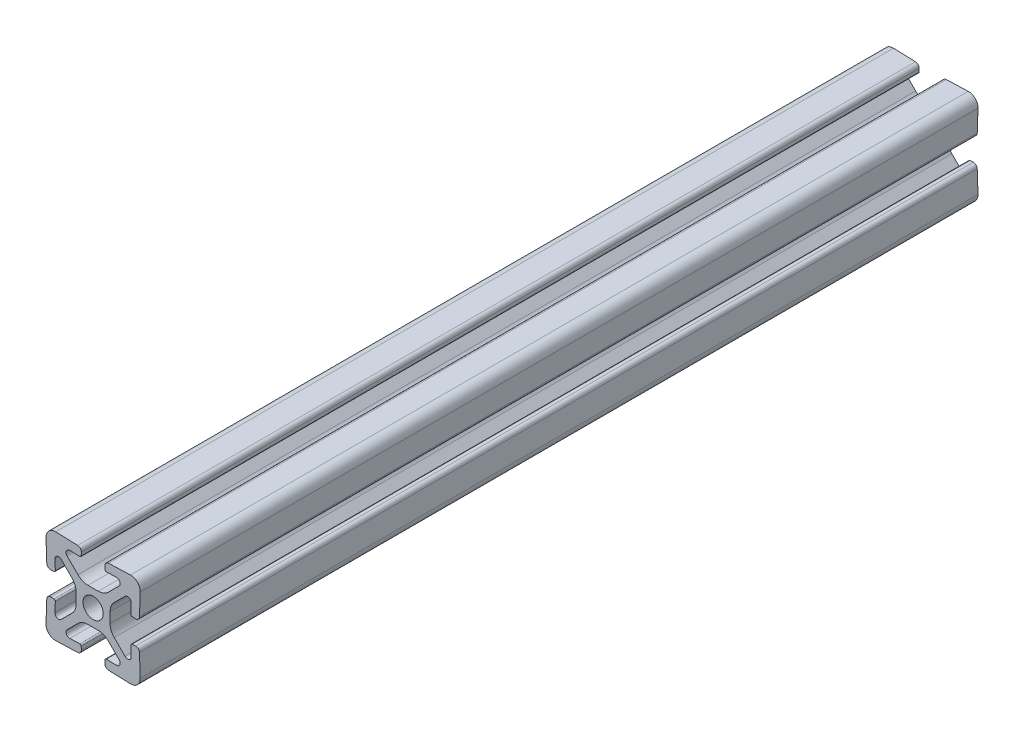
SolidWorks part; units mm, degrees
ref_plane "Front Plane" through (0, 0, 0) normal (0, 0, 1) x (1, 0, 0)
ref_plane "Top Plane" through (0, 0, 0) normal (0, 1, 0) x (1, 0, 0)
ref_plane "Right Plane" through (0, 0, 0) normal (1, 0, 0) x (0, 0, -1)
sketch "Sketch1" plane through (0, 0, 0) normal (0, 0, 1) x (1, 0, 0)
  line L0 (0, 0) -> (0, 10) construction
  line L1 (0, 0) -> (10, 0) construction
  line L2 (0, 0) -> (-10, 10) construction
  line L3 (-7.9302, 9.9988) -> (-3.2721, 9.8361)
  line L4 (-10, 10) -> (0, 10) construction
  line L6 (-2.8352, 8.0198) -> (-4.953, 8.0937)
  line L10 (0, 3.6) -> (-1.1022, 3.6)
  line L11 (-3.2236, 4.4787) -> (-5.5244, 6.7796)
  line L24 (0, 0) -> (-10, 0) construction
  line L25 (-10, 0) -> (0, 0) construction
  line L26 (0, 0) -> (0, -10) construction
  line L27 (-10, -10) -> (-10, 10) construction
  line L28 (0, 10) -> (10, 10) construction
  line L29 (-2.5249, 8.3091) -> (-2.5005, 9.0087)
  line L30 (-10, -10) -> (10, -10) construction
  arc A0 (-9.4142, 9.4142) -> (-7.9302, 9.9988) centre (-8, 8) cw
  arc A5 (-3.2721, 9.8361) -> (-2.5005, 9.0087) centre (-3.3, 9.0366) cw
  arc A6 (-1.1022, 3.6) -> (-3.2236, 4.4787) centre (-1.1022, 6.6) cw
  circle A16 centre (0, 0) radius 2.15
  arc A18 (-5.5244, 6.7796) -> (-4.953, 8.0937) centre (-4.9799, 7.3241) cw
  arc A20 (-2.8352, 8.0198) -> (-2.5249, 8.3091) centre (-2.8247, 8.3196) ccw
  point P15 (0, 0)
  point P42 (-2.3449, 3.6)
  point P80 (-10, 0)
  point P85 (0, -10)
  point P88 (0, -10)
  dimension "D11" = 2
  dimension "D15" = 3
  dimension "Center Hole Diameter" = 4.3
  dimension "D7" = 0.8
  dimension "D8" = 0.3
  dimension "D4" = 0.7701
  dimension "D1" = 45
  dimension "D2" = 2
  dimension "Rail Width" = 20
  dimension "T-Slot Depth" = 6.4
  dimension "D9" = 1.8
  dimension "Rail Height" = 20
  dimension "D23" = 7.2
  dimension "D5" = 11.5
  dimension "T-Slot Width" = 5
  dimension "D3" = 1.775
  dimension "D6" = 9.9598
sketch "Sketch2" plane through (0, 0, 0) normal (1, 0, 0) x (0, 0, -1)
  line L0 (-88.9, 0) -> (88.9, 0)
  line L1 (-88.9, -10) -> (-88.9, 10)
  line L2 (0, 0) -> (0, 10) construction
  line L3 (0, 0) -> (0, 10) construction
  line L4 (88.9, -10) -> (88.9, 10)
  point P0 (-58.9, 0)
  point P3 (0, 0)
  point P7 (58.9, 0)
  point P11 (-88.9, 0)
  point P14 (88.9, 0)
  dimension "D1" = 30
  dimension "Length" = 177.8
sketch "Sketch3" plane through (0, 0, 0) normal (0, 0, 1) x (1, 0, 0)
  line L0 (-2.5249, 8.3091) -> (-2.5005, 9.0087) construction
  line L1 (0, 0) -> (-10, 10) construction
  line L2 (0, 0) -> (-10, 10) construction
  line L5 (-7.9302, 9.9988) -> (-3.2721, 9.8361) construction
  line L6 (-2.8352, 8.0198) -> (-4.953, 8.0937) construction
  line L17 (-2.5249, 8.3091) -> (-2.5005, 9.0087)
  line L19 (-2.8352, 8.0198) -> (-4.953, 8.0937)
  line L20 (0, 0) -> (0, 10) construction
  line L21 (-3.6, 0) -> (-2.15, 0)
  line L22 (-3.6, 0) -> (-3.6, 1.1022)
  line L23 (-4.4787, 3.2236) -> (-6.7796, 5.5244)
  line L42 (-3.2236, 4.4787) -> (-5.5244, 6.7796) construction
  line L43 (0, 3.6) -> (-1.1022, 3.6) construction
  line L44 (-7.9302, 9.9988) -> (-3.2721, 9.8361)
  line L47 (-3.2236, 4.4787) -> (-5.5244, 6.7796)
  line L48 (0, 3.6) -> (-1.1022, 3.6)
  line L59 (0, 3.6) -> (0, 2.15)
  line L60 (-9.9988, 7.9302) -> (-9.8361, 3.2721)
  line L61 (-8.0198, 2.8352) -> (-8.0937, 4.953)
  line L62 (-8.3091, 2.5249) -> (-9.0087, 2.5005)
  arc A0 (-7.9302, 9.9988) -> (-9.4142, 9.4142) centre (-8, 8) ccw construction
  arc A1 (-2.8352, 8.0198) -> (-2.5249, 8.3091) centre (-2.8247, 8.3196) ccw construction
  arc A3 (-2.8352, 8.0198) -> (-2.5249, 8.3091) centre (-2.8247, 8.3196) ccw
  arc A5 (-7.9302, 9.9988) -> (-9.9988, 7.9302) centre (-8, 8) ccw
  circle A13 centre (0, 0) radius 2.15 construction
  arc A14 (0, 2.15) -> (-2.15, 0) centre (0, 0) ccw
  arc A15 (-4.4787, 3.2236) -> (-3.6, 1.1022) centre (-6.6, 1.1022) cw
  arc A16 (-8.0937, 4.953) -> (-6.7796, 5.5244) centre (-7.3241, 4.9799) cw
  arc A17 (-9.0087, 2.5005) -> (-9.8361, 3.2721) centre (-9.0366, 3.3) cw
  arc A18 (-8.0198, 2.8352) -> (-8.3091, 2.5249) centre (-8.3196, 2.8247) cw
  arc A36 (-2.5005, 9.0087) -> (-3.2721, 9.8361) centre (-3.3, 9.0366) ccw construction
  arc A38 (-4.953, 8.0937) -> (-5.5244, 6.7796) centre (-4.9799, 7.3241) ccw construction
  arc A39 (-3.2236, 4.4787) -> (-1.1022, 3.6) centre (-1.1022, 6.6) ccw construction
  arc A41 (-2.5005, 9.0087) -> (-3.2721, 9.8361) centre (-3.3, 9.0366) ccw
  arc A43 (-4.953, 8.0937) -> (-5.5244, 6.7796) centre (-4.9799, 7.3241) ccw
  arc A44 (-3.2236, 4.4787) -> (-1.1022, 3.6) centre (-1.1022, 6.6) ccw
extrude "Boss-Extrude1" add sketch "Sketch3" along normal mid plane 177.8
pattern_circular "CirPattern1" count 4 over 360 about axis through (0, 0, 0) along (0, 0, 1) of "Boss-Extrude1"
ref_plane "Contact Plane 1" through (0, 10, 0) normal (0, 1, 0) x (1, 0, 0)
ref_plane "Contact Plane 2" through (10, 0, 0) normal (1, 0, 0) x (0, 0, -1)
ref_plane "Contact Plane 3" through (0, -10, 0) normal (0, -1, 0) x (-1, 0, 0)
ref_plane "Contact Plane 4" through (-10, 0, 0) normal (-1, 0, 0) x (0, 0, 1)
equation "\"D1@Sketch2\"=\"Rail Width@Sketch1\"*1.5"
equation "\"D1@Boss-Extrude1\" = \"Length@Sketch2\""
